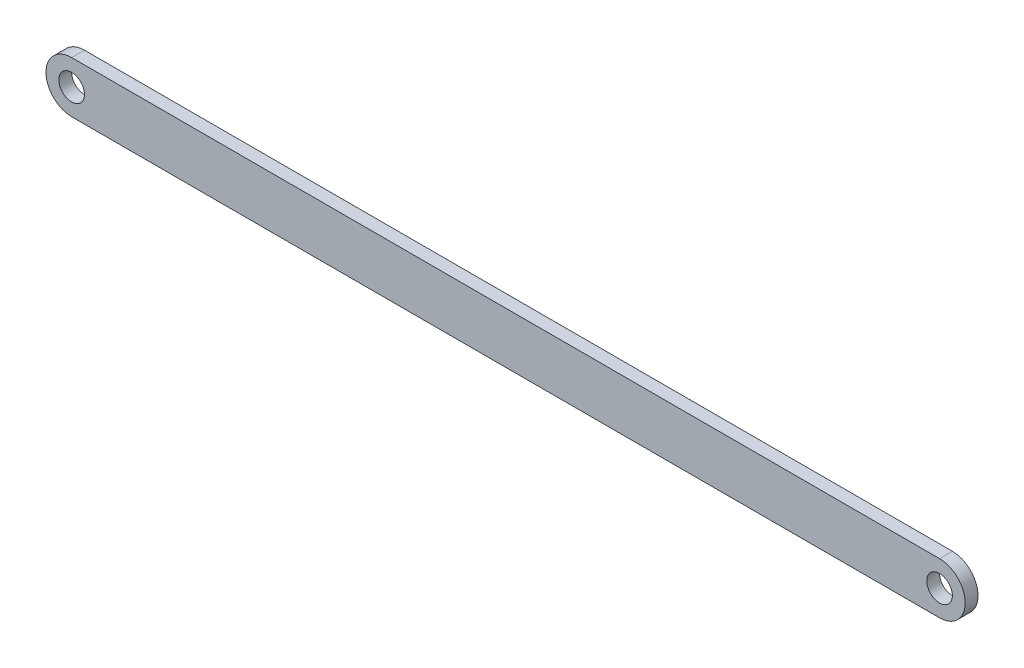
SolidWorks part; units mm, degrees
ref_plane "Plano frontal" through (0, 0, 0) normal (0, 0, 1) x (1, 0, 0)
ref_plane "Plano superior" through (0, 0, 0) normal (0, 1, 0) x (1, 0, 0)
ref_plane "Plano direito" through (0, 0, 0) normal (1, 0, 0) x (0, 0, -1)
sketch "Esboço1" plane through (0, 0, 0) normal (0, 0, 1) x (1, 0, 0)
  line L0 (-33.855, 2) -> (33.855, 2)
  line L1 (-33.855, 0) -> (33.855, 0) construction
  line L2 (-33.855, -2) -> (33.855, -2)
  arc A0 (-33.855, 2) -> (-33.855, -2) centre (-33.855, 0) ccw
  arc A1 (33.855, 2) -> (33.855, -2) centre (33.855, 0) cw
  circle A2 centre (-33.855, 0) radius 1
  circle A3 centre (33.855, 0) radius 1
  point P3 (0, 2)
  dimension "D1" = 67.71
  dimension "D2" = 2
extrude "Ressalto-extrusão1" add sketch "Esboço1" along normal blind 1
